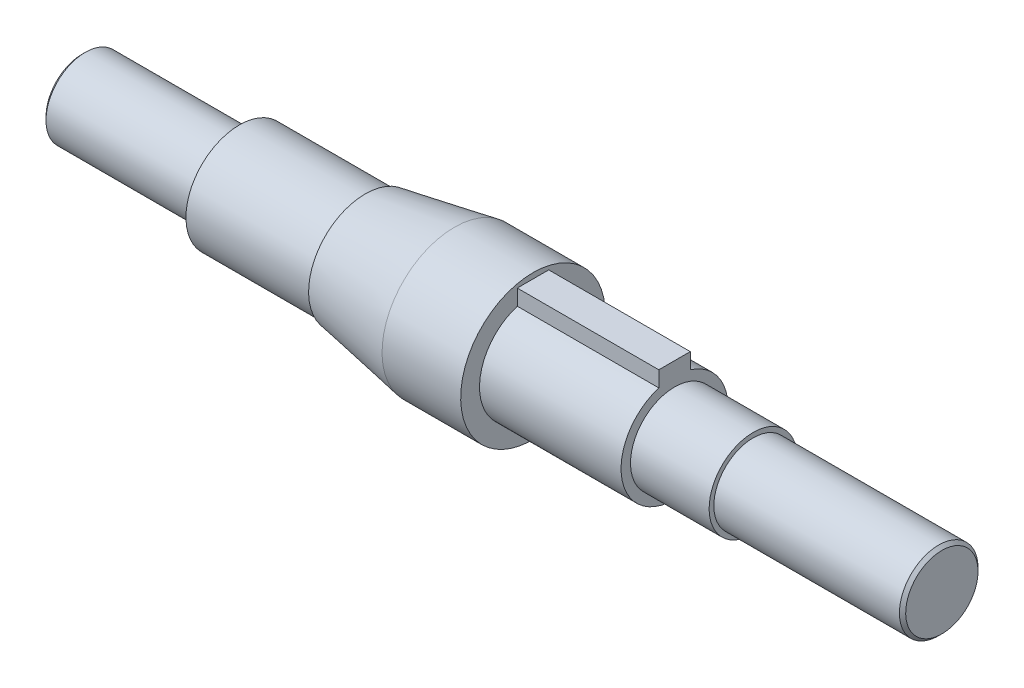
SolidWorks part; units mm, degrees
material "Plain Carbon Steel"
ref_plane "Front Plane" through (0, 0, 0) normal (0, 0, 1) x (1, 0, 0)
ref_plane "Top Plane" through (0, 0, 0) normal (0, 1, 0) x (1, 0, 0)
ref_plane "Right Plane" through (0, 0, 0) normal (1, 0, 0) x (0, 0, -1)
sketch "Sketch1" plane through (0, 0, 0) normal (0, 0, 1) x (1, 0, 0)
  line L0 (-136.6782, 0) -> (-136.6782, 12.5)
  line L1 (-136.6782, 12.5) -> (-86.6782, 12.5)
  line L2 (-86.6782, 12.5) -> (-86.6782, 17)
  line L3 (-86.6782, 17) -> (-46.6782, 17)
  line L4 (-46.6782, 17) -> (-46.6782, 18)
  line L5 (-46.6782, 18) -> (-18.3218, 23)
  line L6 (-18.3218, 23) -> (6.6782, 23)
  line L7 (6.6782, 23) -> (6.6782, 17)
  line L8 (6.6782, 17) -> (51.6782, 17)
  line L9 (51.6782, 17) -> (51.6782, 14)
  line L10 (51.6782, 14) -> (76.6782, 14)
  line L11 (76.6782, 14) -> (76.6782, 12.5)
  line L12 (76.6782, 12.5) -> (136.6782, 12.5)
  line L13 (136.6782, 12.5) -> (136.6782, 0)
  line L14 (136.6782, 0) -> (-136.6782, 0)
  point P6 (-98.8695, 5.8996)
  point P16 (-104.1133, 0)
  point P17 (352.8369, 4.2946)
  point P18 (155.7034, 16.2387)
  point P19 (0, 0)
  point P21 (-109.024, 12.5)
  dimension "D1" = 12.5
  dimension "D2" = 12.5
  dimension "D3" = 14
  dimension "D4" = 17
  dimension "D5" = 25
  dimension "D6" = 17
  dimension "D7" = 50
  dimension "D8" = 45
  dimension "D9" = 25
  dimension "D10" = 60
  dimension "D11" = 18
  dimension "D12" = 10
  dimension "D13" = 40
  dimension "D14" = 23
revolve "Revolve1" add sketch "Sketch1" angle 360 about L14
sketch "Sketch2" plane through (51.6782, 0, 0) normal (1, 0, 0) x (0, 0, -1)
  line L0 (-5, 21.2481) -> (-5, 16.2481)
  line L1 (-5, 16.2481) -> (5, 16.2481)
  line L2 (5, 16.2481) -> (5, 21.2481)
  line L3 (5, 21.2481) -> (-5, 21.2481)
  line L4 (0, 0) -> (0, 21.2481) construction
  circle A0 centre (0, 0) radius 17 construction
  point P7 (2.1563, 16.8627)
  point P10 (3.2714, 16.6823)
  point P11 (0, 0)
  dimension "D1" = 10
  dimension "D2" = 5
extrude "Boss-Extrude1" add sketch "Sketch2" against normal up to surface (45 mm away) up to face at (6.6782, 23, 0)
chamfer "Chamfer1" distance 1 angle 45 2 edges at (-136.6782, 12.5, 0) (136.6782, 12.5, 0)
